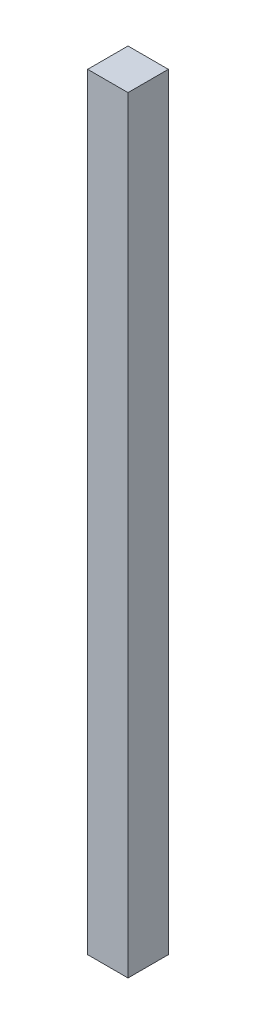
SolidWorks part; units mm, degrees
ref_plane "Front Plane" through (0, 0, 0) normal (0, 0, 1) x (1, 0, 0)
ref_plane "Top Plane" through (0, 0, 0) normal (0, 1, 0) x (1, 0, 0)
ref_plane "Right Plane" through (0, 0, 0) normal (1, 0, 0) x (0, 0, -1)
sketch "Sketch1" plane through (0, 0, 0) normal (0, 1, 0) x (1, 0, 0)
  line L1 (-50, -50) -> (50, -50)
  line L2 (-50, -50) -> (-50, 50)
  line L3 (-50, 50) -> (50, 50)
  line L4 (50, -50) -> (50, 50)
  line L5 (-50, -50) -> (50, 50) construction
  line L6 (-50, 50) -> (50, -50) construction
  point P0 (0, 0)
  dimension "D1" = 100
  dimension "D2" = 100
extrude "Boss-Extrude1" add sketch "Sketch1" along normal blind 1900
